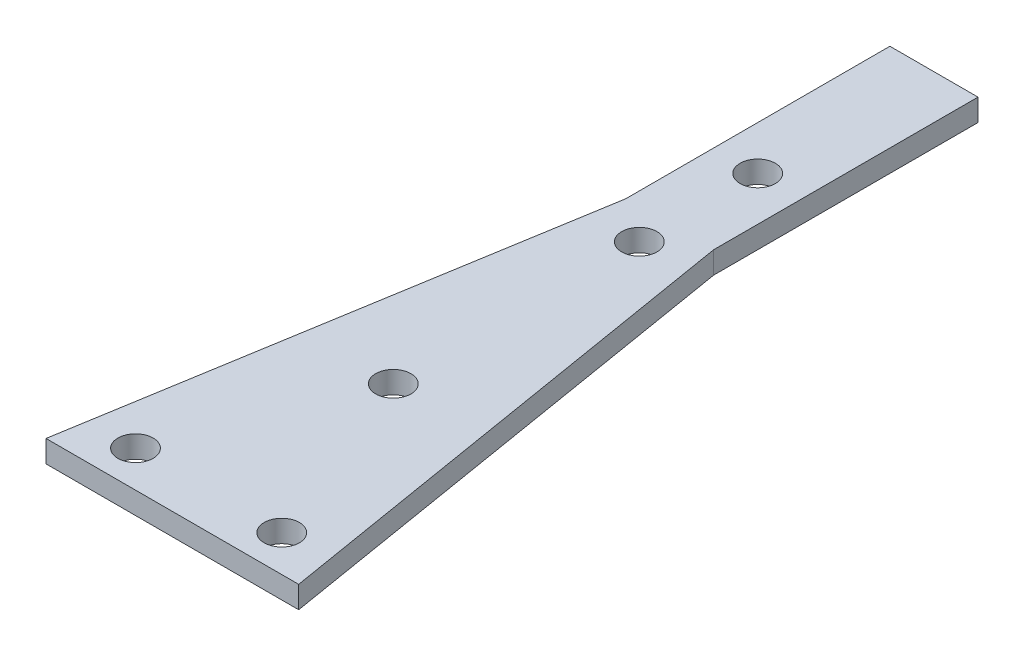
SolidWorks part; units mm, degrees
ref_plane "Front Plane" through (0, 0, 0) normal (0, 0, 1) x (1, 0, 0)
ref_plane "Top Plane" through (0, 0, 0) normal (0, 1, 0) x (1, 0, 0)
ref_plane "Right Plane" through (0, 0, 0) normal (1, 0, 0) x (0, 0, -1)
sketch "Sketch1" plane through (0, 0, 0) normal (0, 1, 0) x (1, 0, 0)
  line L0 (0, 0) -> (38.1, 0) construction
  line L1 (0, 0) -> (0, 46.0502) construction
  line L2 (19.05, 5.08) -> (0.8406, 5.08)
  line L3 (30.48, 46.0502) -> (7.62, 46.0502)
  line L4 (7.62, 46.0502) -> (0.4203, 2.54)
  line L5 (30.48, 46.0502) -> (37.6797, 2.54)
  line L6 (19.05, 0) -> (19.05, 5.08) construction
  line L8 (7.62, 46.0502) -> (12.7, 76.7503)
  line L9 (25.4, 76.7503) -> (30.48, 46.0502)
  line L10 (12.7, 76.7503) -> (25.4, 76.7503)
  line L11 (8.509, 0) -> (8.509, 10.3124) construction
  line L12 (0, 0) -> (8.509, 0) construction
  line L13 (38.1, 0) -> (29.591, 0) construction
  line L14 (29.591, 0) -> (29.591, 10.3124) construction
  line L15 (19.05, 46.0502) -> (19.05, 36.9316) construction
  line L16 (12.7, 76.7503) -> (25.4, 76.7503)
  line L17 (12.7, 76.7503) -> (12.7, 114.8503)
  line L18 (25.4, 76.7503) -> (25.4, 114.8503)
  line L19 (12.7, 114.8503) -> (25.4, 114.8503)
  line L20 (19.05, 5.08) -> (37.2594, 5.08)
  circle A0 centre (8.509, 10.3124) radius 2.54
  circle A1 centre (29.591, 10.3124) radius 2.54
  circle A2 centre (19.05, 36.9316) radius 2.54
  point P8 (19.05, 46.0502)
extrude "Boss-Extrude1" add sketch "Sketch1" along normal blind 3.175
sketch "Sketch4" plane through (0, 0, 0) normal (0, -1, 0) x (1, 0, 0)
  line L2 (19.05, -114.8503) -> (19.05, -89.4503) construction
  line L3 (12.7, -114.8503) -> (25.4, -114.8503) construction
  circle A0 centre (19.05, -72.39) radius 2.54
  circle A1 centre (19.05, -89.4503) radius 2.54
extrude "Cut-Extrude2" cut sketch "Sketch4" against normal blind 25.4
